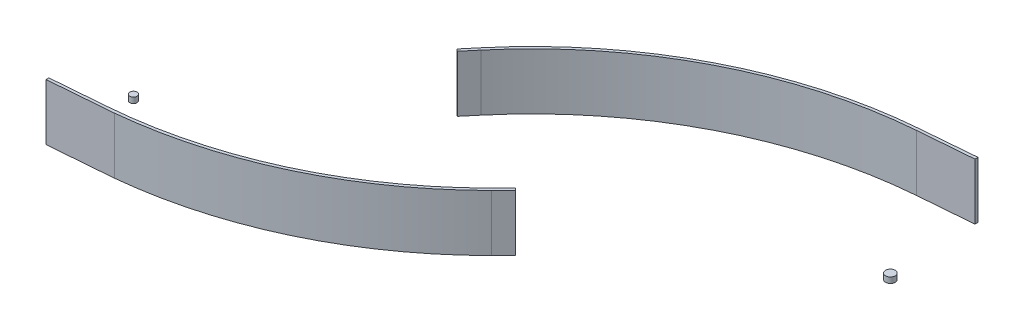
SolidWorks part; units mm, degrees
ref_plane "Front Plane" through (0, 0, 0) normal (0, 0, 1) x (1, 0, 0)
ref_plane "Top Plane" through (0, 0, 0) normal (0, 1, 0) x (1, 0, 0)
ref_plane "Right Plane" through (0, 0, 0) normal (1, 0, 0) x (0, 0, -1)
sketch "Sketch1" plane through (0, 0, 0) normal (0, 1, 0) x (1, 0, 0)
  line L4 (174.462, -419.1241) -> (659.6806, -419.1241) construction
  line L5 (419.6037, -419.1241) -> (296.294, -315.4961) construction
  line L6 (419.6037, -419.1241) -> (529.4864, -528.8812) construction
  line L7 (300.836, -319.3132) -> (281.535, -342.2799)
  line L8 (304.6638, -322.53) -> (285.3628, -345.4968)
  line L9 (285.3628, -345.4968) -> (281.535, -342.2799)
  line L10 (529.4864, -528.8812) -> (550.6875, -507.6558)
  line L11 (525.8284, -525.2274) -> (547.0295, -504.002)
  line L12 (547.0295, -504.002) -> (550.6875, -507.6558)
  line L13 (873.6337, -132.4766) -> (419.6037, -419.1241) construction
  line L14 (0, -593.0702) -> (419.6037, -419.1241) construction
  line L15 (873.6337, -132.4766) -> (873.6337, -130.9766)
  line L16 (873.6337, -130.9766) -> (868.6337, -130.9766)
  line L17 (868.6337, -130.9766) -> (868.6337, -207.6363)
  line L18 (868.6337, -207.6363) -> (868.6337, -133.9766)
  line L19 (868.6337, -133.9766) -> (873.6337, -133.9766)
  line L20 (873.6337, -133.9766) -> (873.6337, -132.4766)
  line L22 (813.6337, -59.9025) -> (909.8959, -52.1057)
  line L23 (813.23, -54.9188) -> (909.8959, -46.7656)
  line L24 (909.8959, -46.7656) -> (909.8959, -52.1057)
  line L27 (76.3114, -744.4781) -> (-35.948, -753.5706)
  line L28 (60, -740.7829) -> (-35.948, -748.5543)
  line L29 (-35.948, -748.5543) -> (-35.948, -753.5706)
  arc A8 (868.6337, -207.6363) -> (419.6037, -419.1241) centre (873.6337, -800.6854) ccw
  arc A9 (0, -593.0702) -> (419.6037, -419.1241) centre (0, 0) ccw
  arc A10 (813.6337, -59.9025) -> (304.6638, -322.53) centre (873.6337, -800.6854) ccw
  arc A11 (813.23, -54.9188) -> (300.836, -319.3132) centre (873.6337, -800.6854) ccw
  arc A12 (60, -740.7829) -> (525.8284, -525.2274) centre (0, 0) ccw
  arc A13 (76.3114, -744.4781) -> (529.4864, -528.8812) centre (0, 0) ccw
  dimension "D2" = 0
  dimension "D5" = 96.2622
  dimension "D9" = 30
  dimension "D4" = 96.2622
  dimension "D3" = 300
  dimension "D8" = 30
  dimension "D10" = 30
  dimension "D11" = 30
  dimension "0" = 0
  dimension "D14" = 1.5
  dimension "D15" = 1.5
  dimension "D16" = 5
extrude "Boss-Extrude3" add sketch "Sketch1" along normal blind 100 contours A11 L7 L9 L8 A10 L22 L24 L23 | A12 L11 L12 L10 A13 L27 L29 L28
sketch "Sketch4" plane through (0, 0, 0) normal (0, -1, 0) x (1, 0, 0)
  line L0 (909.8959, 202.1057) -> (-35.948, 598.5543) construction
  circle A0 centre (909.8959, 202.1057) radius 8.5971
  circle A1 centre (-35.948, 598.5543) radius 6.4166
  dimension "D1" = 150
  dimension "D2" = 150
extrude "Boss-Extrude4" add sketch "Sketch4" against normal blind 10 separate body
sketch "Sketch5" plane through (0, 0, 0) normal (0, -1, 0) x (1, 0, 0)
  circle A1 centre (-35.948, 598.5543) radius 6.4166
  circle A2 centre (-35.948, 598.5543) radius 6.4166
  dimension "D1" = 0
extrude "Boss-Extrude5" add sketch "Sketch5" along normal blind 10
sketch "Sketch6" plane through (0, 10, 0) normal (0, 1, 0) x (1, 0, 0)
  circle A1 centre (-35.948, -598.5543) radius 6.4166
  circle A2 centre (-35.948, -598.5543) radius 6.4166
  dimension "D1" = 0
extrude "Cut-Extrude1" cut sketch "Sketch6" against normal blind 10
sketch "Sketch7" plane through (0, 0, 0) normal (0, -1, 0) x (1, 0, 0)
  circle A1 centre (909.8959, 202.1057) radius 8.5971
  circle A2 centre (909.8959, 202.1057) radius 8.5971
  dimension "D1" = 0
extrude "Boss-Extrude6" add sketch "Sketch7" along normal blind 10
sketch "Sketch8" plane through (0, 10, 0) normal (0, 1, 0) x (1, 0, 0)
  circle A1 centre (909.8959, -202.1057) radius 8.5971
  circle A2 centre (909.8959, -202.1057) radius 8.5971
  dimension "D1" = 0
extrude "Cut-Extrude2" cut sketch "Sketch8" against normal blind 10
